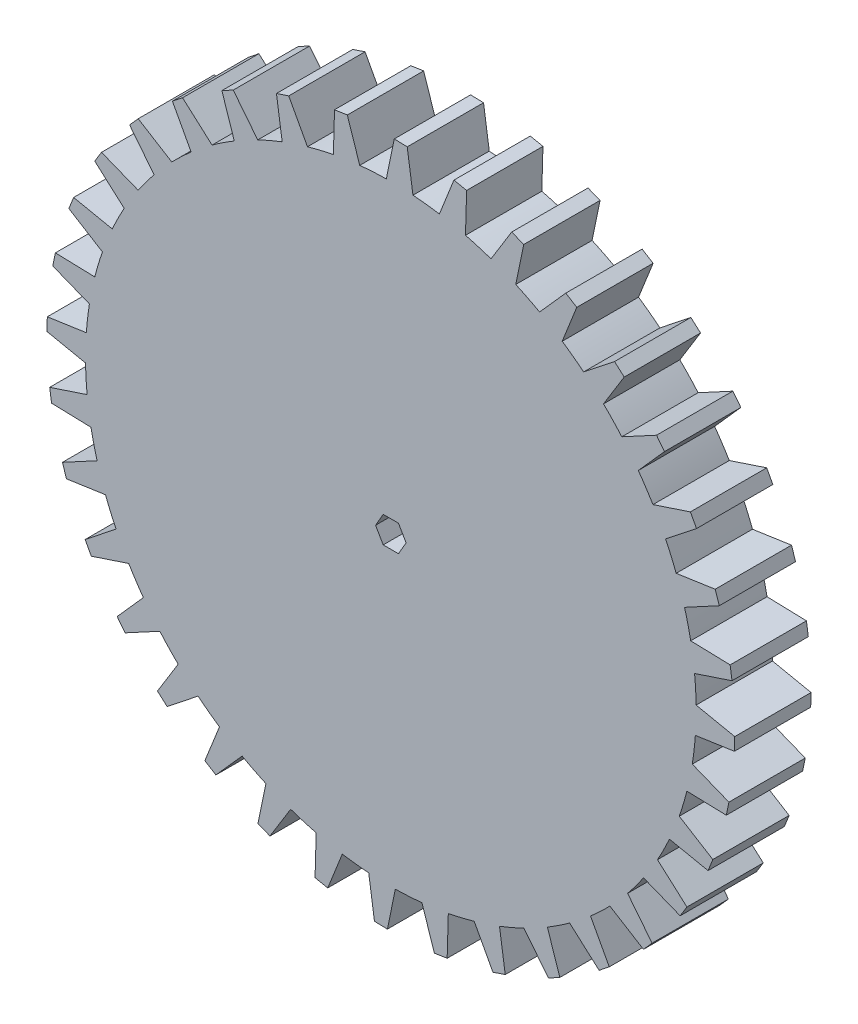
SolidWorks part; units mm, degrees
ref_plane "前视基准面" through (0, 0, 0) normal (0, 0, 1) x (1, 0, 0)
ref_plane "上视基准面" through (0, 0, 0) normal (0, 1, 0) x (1, 0, 0)
ref_plane "右视基准面" through (0, 0, 0) normal (1, 0, 0) x (0, 0, -1)
sketch "草图1" plane through (0, 0, 0) normal (0, 0, 1) x (1, 0, 0)
  line L3 (-9.5608, 49.8922) -> (-9.3716, 56.4527)
  line L4 (-9.3716, 56.4527) -> (-7.242, 56.7652)
  line L5 (-7.242, 56.7652) -> (-5.176, 50.5356)
  line L6 (0.5737, 57.2224) -> (2.7252, 57.1603)
  line L7 (-0.7518, 50.7944) -> (0.5737, 57.2224)
  line L8 (2.7252, 57.1603) -> (3.6781, 50.6667)
  line L9 (10.5016, 56.2534) -> (12.6096, 55.8187)
  line L10 (8.08, 50.1533) -> (10.5016, 56.2534)
  line L11 (12.6096, 55.8187) -> (12.4204, 49.2582)
  line L12 (20.1103, 53.5752) -> (22.1108, 52.7811)
  line L13 (16.6662, 47.9883) -> (20.1103, 53.5752)
  line L14 (22.1108, 52.7811) -> (20.7853, 46.3531)
  line L15 (29.108, 49.2692) -> (30.9402, 48.1397)
  line L16 (24.7461, 44.3652) -> (29.108, 49.2692)
  line L17 (30.9402, 48.1397) -> (28.5186, 42.0396)
  line L18 (37.2213, 43.4661) -> (38.8296, 42.0356)
  line L19 (32.0741, 39.3941) -> (37.2213, 43.4661)
  line L20 (38.8296, 42.0356) -> (35.3855, 36.4487)
  line L21 (44.2037, 36.3423) -> (45.5391, 34.6543)
  line L22 (38.4275, 33.226) -> (44.2037, 36.3423)
  line L23 (45.5391, 34.6543) -> (41.1771, 29.7504)
  line L24 (49.8429, 28.1143) -> (50.8649, 26.2201)
  line L25 (43.6134, 26.0483) -> (49.8429, 28.1143)
  line L26 (50.8649, 26.2201) -> (45.7177, 22.148)
  line L27 (53.9677, 19.0321) -> (54.6452, 16.9891)
  line L28 (47.474, 18.0792) -> (53.9677, 19.0321)
  line L29 (54.6452, 16.9891) -> (48.8691, 13.8728)
  line L30 (56.4527, 9.3716) -> (56.7652, 7.242)
  line L31 (49.8922, 9.5608) -> (56.4527, 9.3716)
  line L32 (56.7652, 7.242) -> (50.5356, 5.176)
  line L33 (57.2224, -0.5737) -> (57.1603, -2.7252)
  line L34 (50.7944, 0.7518) -> (57.2224, -0.5737)
  line L35 (57.1603, -2.7252) -> (50.6667, -3.6781)
  line L36 (56.2534, -10.5016) -> (55.8187, -12.6096)
  line L37 (50.1533, -8.08) -> (56.2534, -10.5016)
  line L38 (55.8187, -12.6096) -> (49.2582, -12.4204)
  line L39 (53.5752, -20.1103) -> (52.7811, -22.1108)
  line L40 (47.9883, -16.6662) -> (53.5752, -20.1103)
  line L41 (52.7811, -22.1108) -> (46.3531, -20.7853)
  line L42 (49.2692, -29.108) -> (48.1397, -30.9402)
  line L43 (44.3652, -24.7461) -> (49.2692, -29.108)
  line L44 (48.1397, -30.9402) -> (42.0396, -28.5186)
  line L45 (43.4661, -37.2213) -> (42.0356, -38.8296)
  line L46 (39.3941, -32.0741) -> (43.4661, -37.2213)
  line L47 (42.0356, -38.8296) -> (36.4487, -35.3855)
  line L48 (36.3423, -44.2037) -> (34.6543, -45.5391)
  line L49 (33.226, -38.4275) -> (36.3423, -44.2037)
  line L50 (34.6543, -45.5391) -> (29.7504, -41.1771)
  line L51 (28.1143, -49.8429) -> (26.2201, -50.8649)
  line L52 (26.0483, -43.6134) -> (28.1143, -49.8429)
  line L53 (26.2201, -50.8649) -> (22.148, -45.7177)
  line L54 (19.0321, -53.9677) -> (16.9891, -54.6452)
  line L55 (18.0792, -47.474) -> (19.0321, -53.9677)
  line L56 (16.9891, -54.6452) -> (13.8728, -48.8691)
  line L57 (9.3716, -56.4527) -> (7.242, -56.7652)
  line L58 (9.5608, -49.8922) -> (9.3716, -56.4527)
  line L59 (7.242, -56.7652) -> (5.176, -50.5356)
  line L60 (-0.5737, -57.2224) -> (-2.7252, -57.1603)
  line L61 (0.7518, -50.7944) -> (-0.5737, -57.2224)
  line L62 (-2.7252, -57.1603) -> (-3.6781, -50.6667)
  line L63 (-10.5016, -56.2534) -> (-12.6096, -55.8187)
  line L64 (-8.08, -50.1533) -> (-10.5016, -56.2534)
  line L65 (-12.6096, -55.8187) -> (-12.4204, -49.2582)
  line L66 (-20.1103, -53.5752) -> (-22.1108, -52.7811)
  line L67 (-16.6662, -47.9883) -> (-20.1103, -53.5752)
  line L68 (-22.1108, -52.7811) -> (-20.7853, -46.3531)
  line L69 (-29.108, -49.2692) -> (-30.9402, -48.1397)
  line L70 (-24.7461, -44.3652) -> (-29.108, -49.2692)
  line L71 (-30.9402, -48.1397) -> (-28.5186, -42.0396)
  line L72 (-37.2213, -43.4661) -> (-38.8296, -42.0356)
  line L73 (-32.0741, -39.3941) -> (-37.2213, -43.4661)
  line L74 (-38.8296, -42.0356) -> (-35.3855, -36.4487)
  line L75 (-44.2037, -36.3423) -> (-45.5391, -34.6543)
  line L76 (-38.4275, -33.226) -> (-44.2037, -36.3423)
  line L77 (-45.5391, -34.6543) -> (-41.1771, -29.7504)
  line L78 (-49.8429, -28.1143) -> (-50.8649, -26.2201)
  line L79 (-43.6134, -26.0483) -> (-49.8429, -28.1143)
  line L80 (-50.8649, -26.2201) -> (-45.7177, -22.148)
  line L81 (-53.9677, -19.0321) -> (-54.6452, -16.9891)
  line L82 (-47.474, -18.0792) -> (-53.9677, -19.0321)
  line L83 (-54.6452, -16.9891) -> (-48.8691, -13.8728)
  line L84 (-56.4527, -9.3716) -> (-56.7652, -7.242)
  line L85 (-49.8922, -9.5608) -> (-56.4527, -9.3716)
  line L86 (-56.7652, -7.242) -> (-50.5356, -5.176)
  line L87 (-57.2224, 0.5737) -> (-57.1603, 2.7252)
  line L88 (-50.7944, -0.7518) -> (-57.2224, 0.5737)
  line L89 (-57.1603, 2.7252) -> (-50.6667, 3.6781)
  line L90 (-56.2534, 10.5016) -> (-55.8187, 12.6096)
  line L91 (-50.1533, 8.08) -> (-56.2534, 10.5016)
  line L92 (-55.8187, 12.6096) -> (-49.2582, 12.4204)
  line L93 (-53.5752, 20.1103) -> (-52.7811, 22.1108)
  line L94 (-47.9883, 16.6662) -> (-53.5752, 20.1103)
  line L95 (-52.7811, 22.1108) -> (-46.3531, 20.7853)
  line L96 (-49.2692, 29.108) -> (-48.1397, 30.9402)
  line L97 (-44.3652, 24.7461) -> (-49.2692, 29.108)
  line L98 (-48.1397, 30.9402) -> (-42.0396, 28.5186)
  line L99 (-43.4661, 37.2213) -> (-42.0356, 38.8296)
  line L100 (-39.3941, 32.0741) -> (-43.4661, 37.2213)
  line L101 (-42.0356, 38.8296) -> (-36.4487, 35.3855)
  line L102 (-36.3423, 44.2037) -> (-34.6543, 45.5391)
  line L103 (-33.226, 38.4275) -> (-36.3423, 44.2037)
  line L104 (-34.6543, 45.5391) -> (-29.7504, 41.1771)
  line L105 (-28.1143, 49.8429) -> (-26.2201, 50.8649)
  line L106 (-26.0483, 43.6134) -> (-28.1143, 49.8429)
  line L107 (-26.2201, 50.8649) -> (-22.148, 45.7177)
  line L108 (-19.0321, 53.9677) -> (-16.9891, 54.6452)
  line L109 (-18.0792, 47.474) -> (-19.0321, 53.9677)
  line L110 (-16.9891, 54.6452) -> (-13.8728, 48.8691)
  line L112 (2.54, 0) -> (1.27, 2.1997)
  line L113 (1.27, 2.1997) -> (-1.27, 2.1997)
  line L114 (-1.27, 2.1997) -> (-2.54, 0)
  line L115 (-2.54, 0) -> (-1.27, -2.1997)
  line L116 (-1.27, -2.1997) -> (1.27, -2.1997)
  line L117 (1.27, -2.1997) -> (2.54, 0)
  circle A0 centre (0, 0) radius 50.8
  circle A2 centre (0, 0) radius 2.54 construction
  dimension "D4" = 36
extrude "凸台-拉伸1" add sketch "草图1" along normal blind 12.7 contours A0 | A0 L8 L6 L7 | A0 L11 L9 L10 | A0 L14 L12 L13 | A0 L5 L4 L3 | A0 L110 L108 L109 | A0 L107 L105 L106 | A0 L104 L102 L103 | A0 L98 L96 L97 | A0 L101 L99 L100 | A0 L92 L90 L91 | A0 L95 L93 L94 | A0 L89 L87 L88 | A0 L86 L84 L85 | A0 L83 L81 L82 | A0 L80 L78 L79 | A0 L77 L75 L76 | A0 L74 L72 L73 | A0 L71 L69 L70 | A0 L68 L66 L67 | A0 L65 L63 L64 | A0 L62 L60 L61 | A0 L59 L57 L58 | A0 L56 L54 L55 | A0 L53 L51 L52 | A0 L50 L48 L49 | A0 L47 L45 L46 | A0 L44 L42 L43 | A0 L41 L39 L40 | A0 L38 L36 L37 | A0 L35 L33 L34 | A0 L32 L30 L31 | A0 L29 L27 L28 | A0 L26 L24 L25 | A0 L23 L21 L22 | A0 L20 L18 L19 | A0 L17 L15 L16
